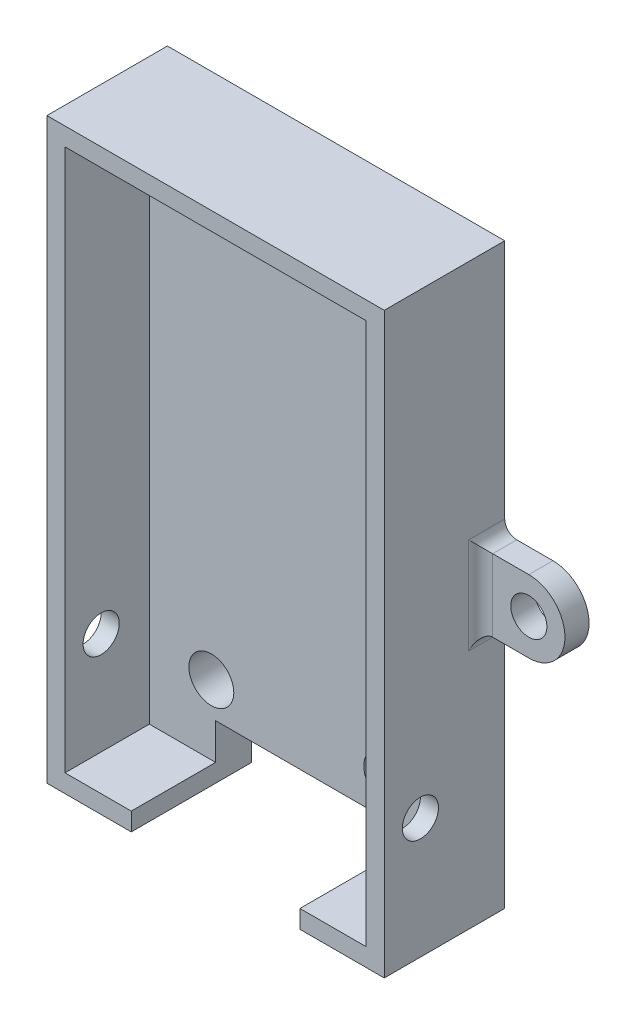
SolidWorks part; units mm, degrees
ref_plane "Plan de face" through (0, 0, 0) normal (0, 0, 1) x (1, 0, 0)
ref_plane "Plan de dessus" through (0, 0, 0) normal (0, 1, 0) x (1, 0, 0)
ref_plane "Plan de droite" through (0, 0, 0) normal (1, 0, 0) x (0, 0, -1)
sketch "Esquisse1" plane through (0, 0, 0) normal (0, 0, 1) x (1, 0, 0)
  line L1 (-12.5, 22.5) -> (12.5, 22.5)
  line L2 (-12.5, 22.5) -> (-12.5, -22.5)
  line L3 (-12.5, -22.5) -> (12.5, -22.5)
  line L4 (12.5, 22.5) -> (12.5, -22.5)
  line L5 (-12.5, 22.5) -> (12.5, -22.5) construction
  line L6 (-12.5, -22.5) -> (12.5, 22.5) construction
  circle A0 centre (-7.3544, -16.7365) radius 1.8635 construction
  circle A1 centre (7.2372, -16.5937) radius 1.9343 construction
  circle A2 centre (-7.1429, 18.056) radius 1.9397 construction
  circle A3 centre (7.3247, 18.0085) radius 1.8546 construction
  circle A4 centre (-7.3544, -16.7365) radius 1.8635
  circle A5 centre (7.2372, -16.5937) radius 1.9343
  circle A6 centre (-7.1429, 18.056) radius 1.9397
  circle A7 centre (7.3247, 18.0085) radius 1.8546
  point P0 (0, 0)
  dimension "D1" = 45
  dimension "D2" = 25
extrude "Boss.-Extru.1" add sketch "Esquisse1" along normal blind 3
sketch "Esquisse2" plane through (0, 0, 0) normal (0, 0, 1) x (1, 0, 0)
  line L4 (7, -22.5) -> (7, -24)
  line L5 (0, -33.7778) -> (0, 28.6546) construction
  line L6 (-7, -22.5) -> (-7, -24)
  line L7 (7, -22.5) -> (12.5, -22.5)
  line L8 (14, -24) -> (14, 24)
  line L9 (14, 24) -> (-14, 24)
  line L10 (-14, 24) -> (-14, -24)
  line L11 (-14, -24) -> (14, -24)
  line L12 (14, -24) -> (14, 24)
  line L13 (14, 24) -> (-14, 24)
  line L14 (-14, 24) -> (-14, -24)
  line L15 (-14, -24) -> (-7, -24)
  line L16 (12.5, -22.5) -> (12.5, 22.5)
  line L17 (12.5, 22.5) -> (-12.5, 22.5)
  line L18 (-12.5, 22.5) -> (-12.5, -22.5)
  line L19 (-12.5, -22.5) -> (12.5, -22.5)
  line L20 (12.5, -22.5) -> (12.5, 22.5)
  line L21 (12.5, 22.5) -> (-12.5, 22.5)
  line L22 (-12.5, 22.5) -> (-12.5, -22.5)
  line L23 (-12.5, -22.5) -> (-7, -22.5)
  line L24 (7, -24) -> (14, -24)
  point P14 (7, -23.25)
  dimension "D3" = 7
  dimension "D1" = 1.5
  dimension "D2" = 0
extrude "Boss.-Extru.2" add sketch "Esquisse2" along normal blind 10
sketch "Esquisse3" plane through (0, 0, 0) normal (1, 0, 0) x (0, 0, -1)
  circle A1 centre (-7, -14) radius 1.5 construction
  circle A2 centre (-7, -14) radius 1.5
extrude "Enlèv. mat.-Extru.1" cut sketch "Esquisse3" against normal through all both and the other way through all
sketch "Esquisse4" plane through (0, 0, 0) normal (0, 0, 1) x (1, 0, 0)
  line L0 (0, -28.542) -> (0, 31.4926) construction
  line L1 (-26.2311, 0) -> (30.3488, 0) construction
  line L2 (-14, 3) -> (-18, 3)
  line L3 (-14, 24) -> (-14, -24) construction
  line L4 (-18, -3) -> (-14, -3)
  line L5 (-14, -3) -> (-14, 3)
  line L6 (18, -3) -> (14, -3)
  line L7 (14, 3) -> (18, 3)
  line L8 (14, -3) -> (14, 3)
  arc A0 (-18, 3) -> (-18, -3) centre (-18, 0) ccw
  circle A1 centre (-18, 0) radius 1.5
  circle A2 centre (18, 0) radius 1.5
  arc A3 (18, 3) -> (18, -3) centre (18, 0) cw
  point P11 (-14, 0)
  dimension "D2" = 3
  dimension "D3" = 3
  dimension "D1" = 4
extrude "Boss.-Extru.3" add sketch "Esquisse4" along normal blind 2
fillet "Congé1" radius 1 6 edges at (14, 3, 1) (14, 0, 2) (14, -3, 1) (-14, 3, 1) (-14, -3, 1) (-14, 0, 2)
sketch "Esquisse5" plane through (0, 0, 0) normal (0, 0, 1) x (1, 0, 0)
  line L0 (-7, -22.5) -> (-7, -19.5)
  line L1 (-7, -19.5) -> (7, -19.5)
  line L2 (7, -19.5) -> (7, -22.5)
  line L3 (7, -22.5) -> (-7, -22.5)
  dimension "D1" = 3
extrude "Enlèv. mat.-Extru.2" cut sketch "Esquisse5" along normal through all
